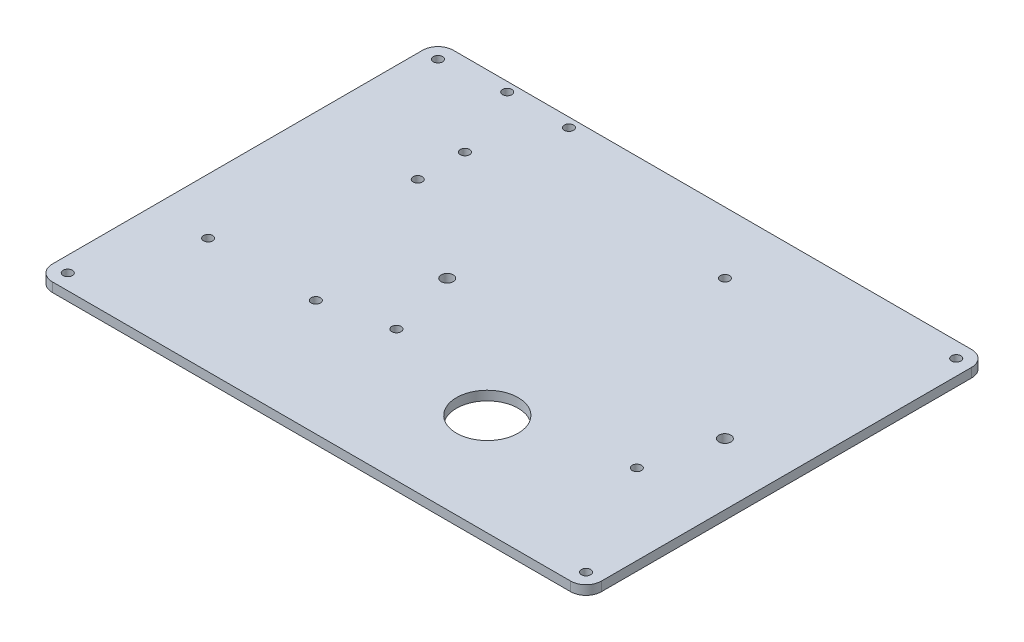
SolidWorks part; units mm, degrees
ref_plane "前视基准面" through (0, 0, 0) normal (0, 0, 1) x (1, 0, 0)
ref_plane "上视基准面" through (0, 0, 0) normal (0, 1, 0) x (1, 0, 0)
ref_plane "右视基准面" through (0, 0, 0) normal (1, 0, 0) x (0, 0, -1)
sketch "草图1" plane through (0, 0, 0) normal (0, 1, 0) x (1, 0, 0)
  line L0 (0, 45) -> (0, 0) construction
  line L1 (0, 0) -> (-38.9711, -22.5) construction
  line L2 (0, 0) -> (38.9711, -22.5) construction
  line L3 (-77.55, 48.7077) -> (-77.55, -32.5856) construction
  line L4 (-95, -27.5) -> (-60.1, -27.5) construction
  line L6 (-95, -30.5) -> (-60.1, -30.5) construction
  line L7 (-98, -27.5) -> (-98, 23) construction
  line L8 (-95, 26) -> (-60.1, 26) construction
  line L9 (-57.1, -27.5) -> (-57.1, 23) construction
  line L10 (-98, -30.5) -> (-57.1, 26) construction
  line L11 (-98, 26) -> (-57.1, -30.5) construction
  line L12 (-108, -65) -> (60, -65)
  line L13 (-113, -60) -> (-113, 60)
  line L14 (-108, 65) -> (60, 65)
  line L15 (65, -60) -> (65, 60)
  line L16 (-113, -65) -> (65, 65) construction
  line L17 (-113, 65) -> (65, -65) construction
  circle A0 centre (0, 0) radius 45 construction
  circle A1 centre (0, 45) radius 1.5
  circle A2 centre (-38.9711, -22.5) radius 1.5
  circle A3 centre (38.9711, -22.5) radius 1.5
  circle A4 centre (-45, 0) radius 1.95
  circle A5 centre (45, 0) radius 1.95
  circle A6 centre (-95, -27.5) radius 1.5
  circle A7 centre (-60.1, -27.5) radius 1.5
  circle A8 centre (-77.55, 23) radius 1.5
  circle A9 centre (0, 0) radius 50 construction
  arc A10 (-95, -30.5) -> (-98, -27.5) centre (-95, -27.5) cw construction
  arc A11 (-60.1, -30.5) -> (-57.1, -27.5) centre (-60.1, -27.5) ccw construction
  arc A12 (-57.1, 23) -> (-60.1, 26) centre (-60.1, 23) ccw construction
  arc A13 (-98, 23) -> (-95, 26) centre (-95, 23) cw construction
  arc A14 (-108, -65) -> (-113, -60) centre (-108, -60) cw
  arc A15 (60, -65) -> (65, -60) centre (60, -60) ccw
  arc A16 (65, 60) -> (60, 65) centre (60, 60) ccw
  arc A17 (-113, 60) -> (-108, 65) centre (-108, 60) cw
  circle A18 centre (-108, 60) radius 1.5
  circle A19 centre (60, 60) radius 1.5
  circle A20 centre (60, -60) radius 1.5
  circle A21 centre (-108, -60) radius 1.5
  circle A22 centre (0, -32) radius 10
  point P20 (-77.55, -27.5)
  point P23 (-77.55, -2.25)
  point P43 (-24, 0)
  dimension "D1" = 90
  dimension "D4" = 3
  dimension "D5" = 3
  dimension "D6" = 3
  dimension "D7" = 3.9
  dimension "D8" = 3.9
  dimension "D10" = 3
  dimension "D11" = 3
  dimension "D14" = 100
  dimension "D16" = 3
  dimension "D19" = 3
  dimension "D23" = 5
  dimension "D24" = 3
  dimension "D25" = 3
  dimension "D26" = 3
  dimension "D27" = 3
  dimension "D29" = 20
  dimension "D2" = 120
  dimension "D3" = 120
  dimension "D9" = 77.55
  dimension "D12" = 50.5
  dimension "D13" = 34.9
  dimension "D15" = 3
  dimension "D17" = 40.9
  dimension "D18" = 23
  dimension "D20" = 130
  dimension "D21" = 15
  dimension "D22" = 65
  dimension "D28" = 32
extrude "凸台-拉伸1" add sketch "草图1" along normal blind 3
sketch "草图2" plane through (0, 3, 0) normal (0, 1, 0) x (1, 0, 0)
  line L0 (60, 65) -> (-108, 65) construction
  line L1 (-87.55, 38.3) -> (-67.55, 38.3) construction
  line L2 (-87.55, 38.3) -> (-87.55, 62) construction
  line L3 (-87.55, 62) -> (-67.55, 62) construction
  line L4 (-67.55, 38.3) -> (-67.55, 62) construction
  line L5 (-87.55, 38.3) -> (-67.55, 62) construction
  line L6 (-87.55, 62) -> (-67.55, 38.3) construction
  line L8 (-113, 60) -> (-113, -60) construction
  circle A0 centre (-87.55, 62) radius 1.5
  circle A1 centre (-67.55, 62) radius 1.5
  circle A2 centre (-77.55, 38.3) radius 1.5
  point P0 (-77.55, 50.15)
  dimension "D3" = 3
  dimension "D4" = 3
  dimension "D5" = 3
  dimension "D1" = 20
  dimension "D2" = 23.7
  dimension "D6" = 3
  dimension "D7" = 35.45
extrude "切除-拉伸1" cut sketch "草图2" against normal through all
